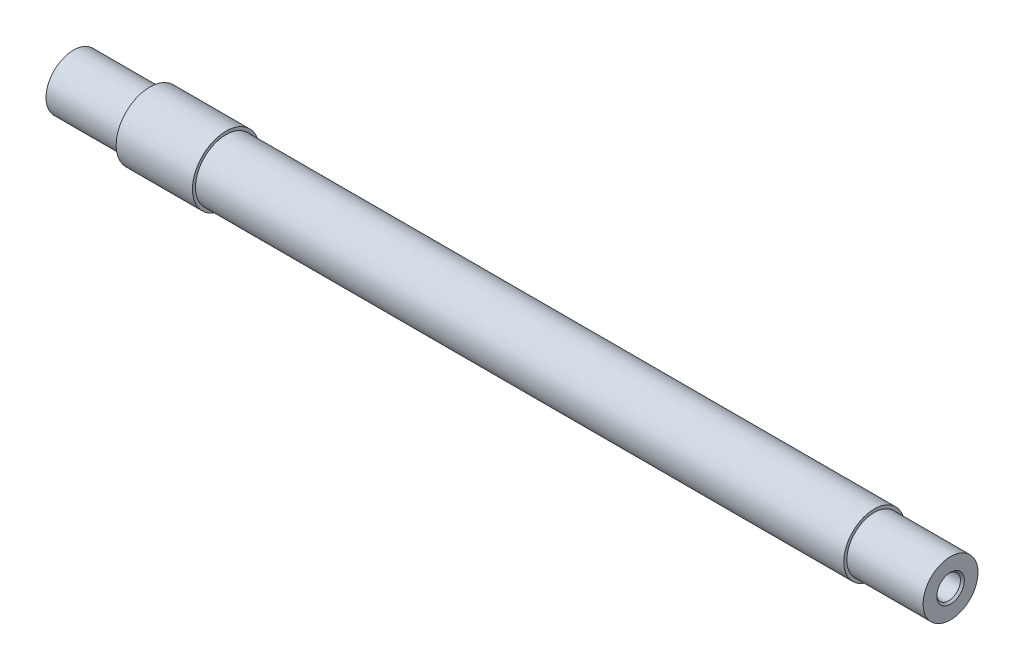
SolidWorks part; units mm, degrees
material "AISI 4340 Aço, normalizado"
ref_plane "Plano frontal" through (0, 0, 0) normal (0, 0, 1) x (1, 0, 0)
ref_plane "Plano superior" through (0, 0, 0) normal (0, 1, 0) x (1, 0, 0)
ref_plane "Plano direito" through (0, 0, 0) normal (1, 0, 0) x (0, 0, -1)
sketch "Esboço1" plane through (0, 0, 0) normal (0, 0, 1) x (1, 0, 0)
  line L0 (0, 0) -> (0, 18)
  line L8 (575, 18) -> (575, 0)
  line L9 (575, 0) -> (0, 0)
  line L10 (0, 18) -> (50, 18)
  line L11 (50, 18) -> (50, 22)
  line L12 (50, 22) -> (100, 22)
  line L13 (100, 22) -> (100, 20)
  line L14 (100, 20) -> (525, 20)
  line L15 (525, 20) -> (525, 18)
  line L16 (525, 18) -> (575, 18)
  dimension "D1" = 575
  dimension "D2" = 2
  dimension "D3" = 20
  dimension "D4" = 50
  dimension "D5" = 2
  dimension "D6" = 50
revolve "Revolução1" add sketch "Esboço1" angle 360 about L9
fillet "Filete1" [suppressed] radius 3
fillet "Filete2" [suppressed] radius 2
hole_wizard "Furo roscado de M181" positions "3DSketch1" profile "Esboço3" tap size "M18" standard "ISO"
sketch3d "3DSketch1"
  line L0 (525, 0, 0) -> (575, 0, 0) construction
  line L1 (0, 0, 0) -> (50, 0, 0) construction
  point P55 (0, 0, 0)
  point P61 (575, 0, 0)
  point P65 (0, 0, 0)
  point P70 (0, 0, 0)
  point P72 (0, 0, 0)
  point P75 (0, 0, 0)
sketch "Esboço3" plane through (0, 0, 0) normal (0, 1, 0) x (0, 0, 1)
  line L0 (0, 0) -> (0, 29.6567)
  line L1 (0, 29.6567) -> (7.75, 25)
  line L2 (7.75, 25) -> (7.75, 1.275)
  line L3 (7.75, 1.275) -> (9.025, 0)
  line L5 (9.025, 0) -> (0, 0)
  line L6 (-7.75, 1.275) -> (-9.025, 0) construction
  line L10 (0, 29.6567) -> (-7.75, 25) construction
  line L11 (0, -6.35) -> (0, 107.95) construction
  dimension "Tap Drill Dia." = 15.5
  dimension "Tap Drill Depth" = 25
  dimension "Near C'Sink Dia." = 18.05
  dimension "Near C'Sink Angle" = 90
  dimension "Drill Angle" = 118
cosmetic thread "Rosca de furo4"
cosmetic thread "Rosca de furo5"
cosmetic thread "Rosca de furo6"
cosmetic thread "Rosca de furo7"
cosmetic thread "Rosca de furo8"
equation "\"D1@Esboço1\"=475+100"
